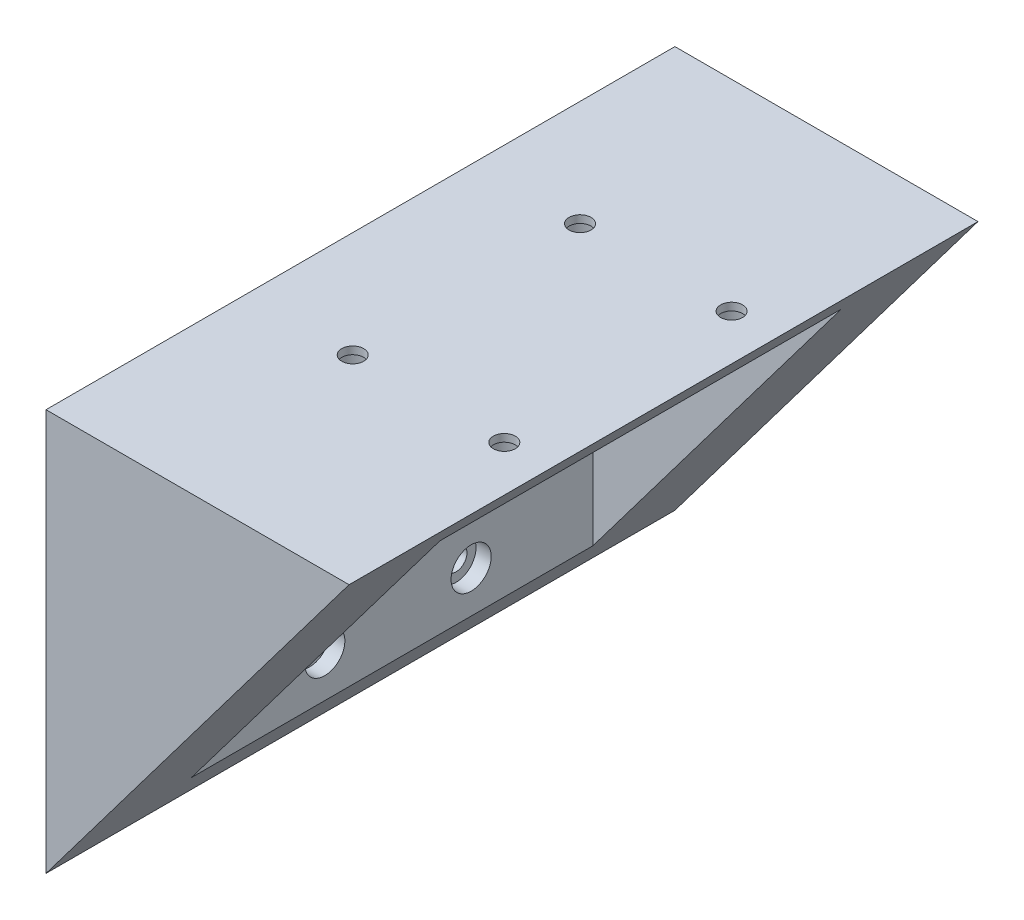
SolidWorks part; units mm, degrees
ref_plane "前视基准面" through (0, 0, 0) normal (0, 0, 1) x (1, 0, 0)
ref_plane "上视基准面" through (0, 0, 0) normal (0, 1, 0) x (1, 0, 0)
ref_plane "右视基准面" through (0, 0, 0) normal (1, 0, 0) x (0, 0, -1)
sketch "草图1" plane through (0, 0, 0) normal (0, 0, 1) x (1, 0, 0)
  line L0 (0, 2.3331) -> (0, -50.6669)
  line L1 (0, 2.3331) -> (40, 2.3331)
  line L2 (40, 2.3331) -> (0, -50.6669)
  dimension "D1" = 53
  dimension "D2" = 40
extrude "凸台-拉伸1" add sketch "草图1" along normal blind 83
ref_plane "基准面1" through (0, 0, 41.5) normal (0, 0, 1) x (1, 0, 0)
sketch "草图3" plane through (0, 0, 41.5) normal (0, 0, 1) x (1, 0, 0)
  line L0 (36.9811, -1.6669) -> (4.1736, -1.6669)
  line L1 (0, -50.6669) -> (40, 2.3331) construction
  line L2 (4.1736, -1.6669) -> (4.1736, -45.1369)
  line L3 (4.1736, -45.1369) -> (36.9811, -1.6669)
  line L5 (40, 2.3331) -> (0, 2.3331) construction
  line L11 (0, 2.3331) -> (0, -50.6669) construction
  dimension "D1" = 47.47
  dimension "D2" = 4
extrude "切除-拉伸1" cut sketch "草图3" against normal mid plane 53
sketch "草图4" plane through (4.1736, 0, 0) normal (1, 0, 0) x (0, 0, -1)
  line L0 (-40.755, -23.1869) -> (-40.76, -45.1369) construction
  line L1 (-60.01, -45.1369) -> (-21.51, -45.1369) construction
  line L2 (-60.01, -45.1369) -> (-60.01, -23.1869) construction
  line L3 (-60.01, -23.1869) -> (-21.51, -23.1869) construction
  line L4 (-21.51, -45.1369) -> (-21.51, -23.1869) construction
  line L6 (-83, -50.6669) -> (-83, 2.3331) construction
  line L7 (-15, -45.1369) -> (-68, -45.1369) construction
  line L8 (-50.38, -23.1869) -> (-50.38, -45.1369) construction
  line L9 (-60.01, -28.6869) -> (-21.51, -28.6869) construction
  line L10 (-60.01, -35.7919) -> (-21.51, -35.7919) construction
  line L11 (-60.005, -23.1869) -> (-40.755, -23.1869) construction
  line L12 (-50.38, -39.6369) -> (-31.0686, -39.6369) construction
  line L13 (-31.0686, -28.6869) -> (-31.0686, -39.6369) construction
  line L14 (-50.38, -28.6869) -> (-31.0686, -28.6869) construction
  circle A2 centre (-31.0686, -39.6369) radius 1.45
  circle A3 centre (-31.0686, -28.6869) radius 1.45
  circle A4 centre (-50.38, -28.6869) radius 1.45
  circle A5 centre (-50.38, -39.6369) radius 1.45
  point P0 (-41.5, -35.7919)
  dimension "D5" = 5.5
  dimension "D8" = 2.9
  dimension "D9" = 2.9
  dimension "D10" = 2.9
  dimension "D11" = 2.9
  dimension "D1" = 38.5
  dimension "D2" = 21.95
  dimension "D3" = 9.63
  dimension "D4" = 5.5
  dimension "D6" = 19.25
  dimension "D7" = 22.99
extrude "切除-拉伸3" cut sketch "草图4" against normal blind 10
sketch "草图5" plane through (0, -1.6669, 0) normal (0, -1, 0) x (1, 0, 0)
  line L0 (22, 41.5) -> (-22, 41.5) construction
  line L1 (13.9811, 26.5) -> (33.9811, 26.5) construction
  line L2 (13.9811, 26.5) -> (13.9811, 56.5) construction
  line L3 (13.9811, 56.5) -> (33.9811, 56.5) construction
  line L4 (33.9811, 26.5) -> (33.9811, 56.5) construction
  line L5 (13.9811, 26.5) -> (33.9811, 56.5) construction
  line L6 (13.9811, 56.5) -> (33.9811, 26.5) construction
  line L8 (36.9811, 15) -> (36.9811, 68) construction
  circle A2 centre (13.9811, 56.5) radius 1.45
  circle A3 centre (33.9811, 56.5) radius 1.45
  circle A4 centre (13.9811, 26.5) radius 1.45
  circle A5 centre (33.9811, 26.5) radius 1.45
  point P0 (23.9811, 41.5)
  dimension "D1" = 20
  dimension "D4" = 2.9
  dimension "D5" = 2.9
  dimension "D6" = 2.9
  dimension "D7" = 2.9
  dimension "D2" = 30
  dimension "D3" = 3
extrude "切除-拉伸4" cut sketch "草图5" against normal blind 10
sketch "草图6" plane through (4.1736, 0, 0) normal (1, 0, 0) x (0, 0, -1)
  circle A0 centre (-50.38, -28.6869) radius 2.65
  circle A1 centre (-31.0686, -28.6869) radius 2.65
  circle A2 centre (-50.38, -39.6369) radius 2.65
  circle A3 centre (-31.0686, -39.6369) radius 2.65
  dimension "D1" = 5.3
  dimension "D2" = 5.3
  dimension "D3" = 5.3
  dimension "D4" = 5.3
extrude "切除-拉伸5" cut sketch "草图6" against normal blind 2
sketch "草图7" plane through (0, -1.6669, 0) normal (0, -1, 0) x (1, 0, 0)
  circle A0 centre (13.9811, 56.5) radius 2.8
  circle A1 centre (33.9811, 56.5) radius 2.8
  circle A2 centre (13.9811, 26.5) radius 2.8
  circle A3 centre (33.9811, 26.5) radius 2.8
  dimension "D1" = 5.6
  dimension "D2" = 5.6
  dimension "D3" = 5.6
  dimension "D4" = 5.6
extrude "切除-拉伸6" cut sketch "草图7" against normal blind 3
